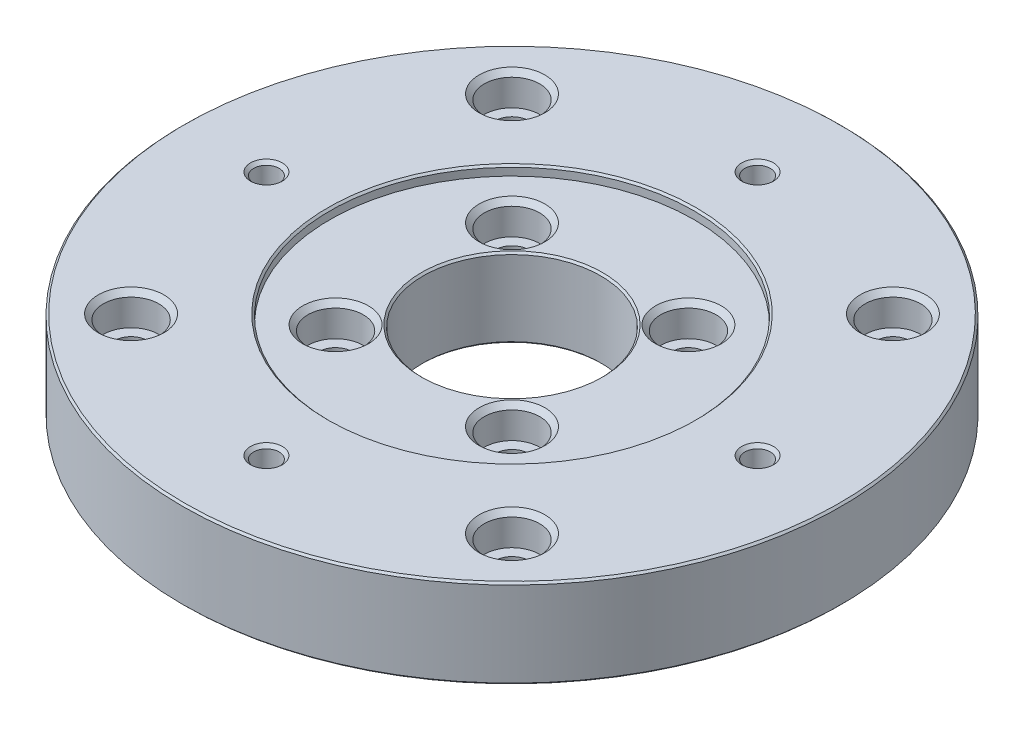
SolidWorks part; units mm, degrees
material "Plain Carbon Steel"
ref_plane "Front Plane" through (0, 0, 0) normal (0, 0, 1) x (1, 0, 0)
ref_plane "Top Plane" through (0, 0, 0) normal (0, 1, 0) x (1, 0, 0)
ref_plane "Right Plane" through (0, 0, 0) normal (1, 0, 0) x (0, 0, -1)
sketch "Sketch1" plane through (0, 0, 0) normal (0, 1, 0) x (1, 0, 0)
  circle A0 centre (0, 0) radius 66.04
  dimension "D1" = 132.08
extrude "Boss-Extrude1" add sketch "Sketch1" along normal blind 17.78
sketch "Sketch2" plane through (0, 17.78, 0) normal (0, 1, 0) x (1, 0, 0)
  circle A0 centre (0, 0) radius 36.4998
  dimension "D1" = 72.9996
extrude "Cut-Extrude1" cut sketch "Sketch2" against normal blind 1.905
sketch "Sketch3" plane through (0, 15.875, 0) normal (0, 1, 0) x (1, 0, 0)
  circle A0 centre (0, 0) radius 17.78
  dimension "D1" = 35.56
extrude "Cut-Extrude2" cut sketch "Sketch3" against normal blind 19.05 and the other way through all
hole_wizard "1/4-20 Tapped Hole1" positions "Sketch4" profile "Sketch5" tap size "1/4-20" standard "ANSI Inch" end condition through all
sketch "Sketch4" plane through (0, 17.78, 0) normal (0, 1, 0) x (1, 0, 0)
  circle A0 centre (0, 0) radius 49.2125 construction
  point P9 (0, 49.2125)
  point P11 (49.2125, 0)
  point P13 (0, -49.2125)
  point P15 (-49.2125, 0)
  dimension "D1" = 98.425
sketch "Sketch5" plane through (0, 17.78, -49.2125) normal (1, 0, 0) x (0, 0, 1)
  line L0 (0, 0) -> (0, 17.78)
  line L1 (0, 17.78) -> (3.1877, 17.78)
  line L2 (2.5527, 17.145) -> (2.5527, 0.635)
  line L3 (2.5527, 0.635) -> (3.1877, 0)
  line L5 (3.1877, 0) -> (0, 0)
  line L6 (-2.5527, 0.635) -> (-3.1877, 0) construction
  line L7 (3.1877, 17.78) -> (2.5527, 17.145)
  line L8 (-3.1877, 17.78) -> (-2.5527, 17.145) construction
  line L11 (0, -6.35) -> (0, 107.95) construction
  dimension "Thru Tap Drill Dia." = 5.1054
  dimension "Thru Tap Drill Depth" = 17.78
  dimension "Near C'Sink Dia." = 6.3754
  dimension "Near C'Sink Angle" = 90
  dimension "Far C'Sink Dia." = 6.3754
  dimension "Far C'Sink Angle" = 90
cosmetic thread "Hole Thread5" parameters "D2"=6.35
cosmetic thread "Hole Thread6" parameters "D2"=6.35
cosmetic thread "Hole Thread7" parameters "D2"=6.35
cosmetic thread "Hole Thread8" parameters "D2"=6.35
hole_wizard "CBORE for 1/4 Socket Head Cap Screw1" positions "Sketch6" profile "Sketch7" counterbore size "1/4" standard "ANSI Inch" end condition through all
sketch "Sketch6" plane through (0, 15.875, 0) normal (0, 1, 0) x (1, 0, 0)
  line L1 (-17.6777, -17.6777) -> (17.6777, -17.6777) construction
  line L2 (-17.6777, -17.6777) -> (-17.6777, 17.6777) construction
  line L3 (-17.6777, 17.6777) -> (17.6777, 17.6777) construction
  line L4 (17.6777, -17.6777) -> (17.6777, 17.6777) construction
  line L5 (-17.6777, -17.6777) -> (17.6777, 17.6777) construction
  line L6 (-17.6777, 17.6777) -> (17.6777, -17.6777) construction
  point P1 (0, 0)
  point P2 (17.6777, 17.6777)
  point P27 (-17.6777, -17.6777)
  point P28 (-17.6777, 17.6777)
  point P29 (17.6777, -17.6777)
  dimension "D1" = 50
sketch "Sketch7" plane through (0, 15.875, 0) normal (1, 0, 0) x (0, 0, 1)
  line L0 (0, 0) -> (0, 15.875)
  line L1 (3.3782, 15.24) -> (4.0132, 15.875)
  line L2 (5.5562, 6.35) -> (3.3782, 6.35)
  line L3 (3.3782, 6.35) -> (3.3782, 15.24)
  line L5 (5.5562, 6.35) -> (5.5562, 1.0325)
  line L6 (5.5562, 1.0325) -> (6.5888, 0)
  line L7 (6.5888, 0) -> (0, 0)
  line L8 (-5.5562, 1.0325) -> (-6.5888, 0) construction
  line L11 (0, -6.35) -> (0, 107.95) construction
  line L12 (4.0132, 15.875) -> (0, 15.875)
  line L13 (-3.3782, 15.24) -> (-4.0132, 15.875) construction
  dimension "Thru Hole Dia." = 6.7564
  dimension "Thru Hole Depth" = 15.875
  dimension "C'Bore Dia." = 11.1125
  dimension "C'Bore Depth" = 6.35
  dimension "Near C'Sink Dia." = 13.1775
  dimension "Near C'Sink Angle" = 90
  dimension "Far C'Sink Dia." = 8.0264
  dimension "Far C'Sink Angle" = 90
chamfer "Chamfer1" distance 0.381 angle 45 5 edges at (0, 0, 66.04) (0, 17.78, 66.04) (0, 0, 17.78) (0, 17.78, 36.4998) (0, 15.875, 17.78)
hole_wizard "CBORE for 1/4 Socket Head Cap Screw2" positions "Sketch8" profile "Sketch9" counterbore size "1/4" standard "ANSI Inch" end condition through all
sketch "Sketch8" plane through (0, 17.78, 0) normal (0, 1, 0) x (1, 0, 0)
  line L1 (-38.1661, 38.1661) -> (38.1661, 38.1661) construction
  line L2 (-38.1661, 38.1661) -> (-38.1661, -38.1661) construction
  line L3 (-38.1661, -38.1661) -> (38.1661, -38.1661) construction
  line L4 (38.1661, 38.1661) -> (38.1661, -38.1661) construction
  line L5 (-38.1661, 38.1661) -> (38.1661, -38.1661) construction
  line L6 (-38.1661, -38.1661) -> (38.1661, 38.1661) construction
  point P1 (0, 0)
  point P2 (38.1661, -38.1661)
  point P27 (-38.1661, 38.1661)
  point P28 (-38.1661, -38.1661)
  point P29 (38.1661, 38.1661)
  dimension "D1" = 107.95
sketch "Sketch9" plane through (0, 17.78, 0) normal (1, 0, 0) x (0, 0, 1)
  line L0 (0, 0) -> (0, 17.78)
  line L1 (3.3782, 17.145) -> (4.0132, 17.78)
  line L2 (5.5562, 6.35) -> (3.3782, 6.35)
  line L3 (3.3782, 6.35) -> (3.3782, 17.145)
  line L5 (5.5562, 6.35) -> (5.5562, 1.0325)
  line L6 (5.5562, 1.0325) -> (6.5888, 0)
  line L7 (6.5888, 0) -> (0, 0)
  line L8 (-5.5562, 1.0325) -> (-6.5888, 0) construction
  line L11 (0, -6.35) -> (0, 107.95) construction
  line L12 (4.0132, 17.78) -> (0, 17.78)
  line L13 (-3.3782, 17.145) -> (-4.0132, 17.78) construction
  dimension "Thru Hole Dia." = 6.7564
  dimension "Thru Hole Depth" = 17.78
  dimension "C'Bore Dia." = 11.1125
  dimension "C'Bore Depth" = 6.35
  dimension "Near C'Sink Dia." = 13.1775
  dimension "Near C'Sink Angle" = 90
  dimension "Far C'Sink Dia." = 8.0264
  dimension "Far C'Sink Angle" = 90
